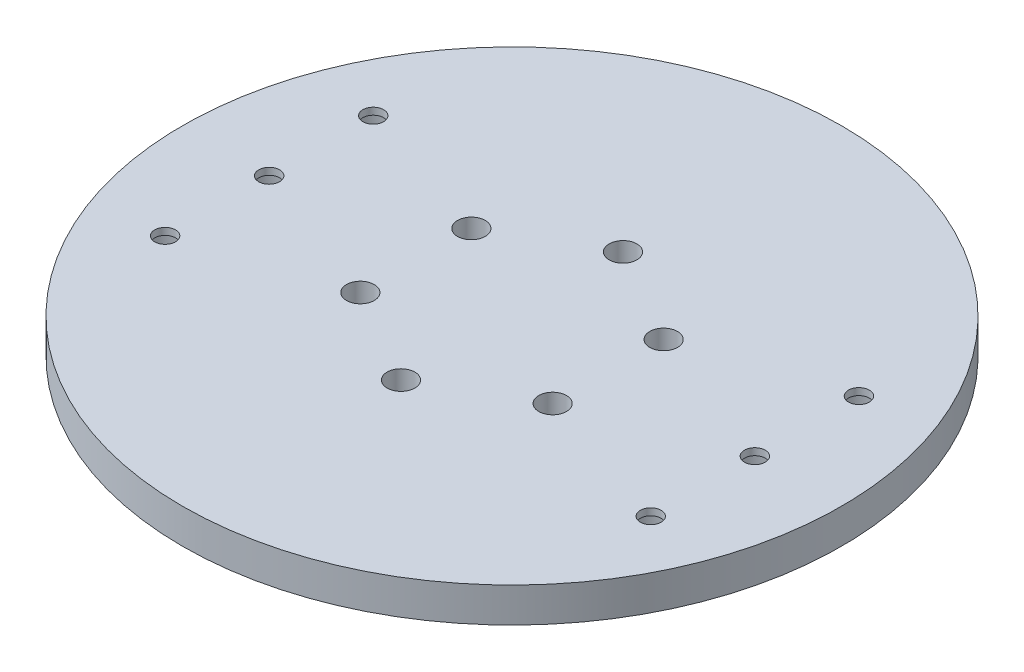
SolidWorks part; units mm, degrees
ref_plane "Alzado" through (0, 0, 0) normal (0, 0, 1) x (1, 0, 0)
ref_plane "Planta" through (0, 0, 0) normal (0, 1, 0) x (1, 0, 0)
ref_plane "Vista lateral" through (0, 0, 0) normal (1, 0, 0) x (0, 0, -1)
sketch "Croquis1" plane through (0, 0, 0) normal (0, 1, 0) x (1, 0, 0)
  circle A0 centre (0, 0) radius 24.5
  dimension "D1" = 49
extrude "Saliente-Extruir1" add sketch "Croquis1" along normal blind 3.7
sketch "Croquis2" plane through (0, 3.7, 0) normal (0, 1, 0) x (1, 0, 0)
  circle A0 centre (0, 0) radius 16 construction
  circle A1 centre (0, 16) radius 2
  dimension "D1" = 32
  dimension "D2" = 4
extrude "Cortar-Extruir1" cut sketch "Croquis2" against normal through all
pattern_circular "MatrizC1" count 6 over 360 about axis through (0, 0, 0) along (0, 1, 0) of "Cortar-Extruir1"
sketch "Croquis3" plane through (0, 3.7, 0) normal (0, 1, 0) x (1, 0, 0)
  circle A1 centre (0, 0) radius 47.5
  circle A2 centre (13.8564, 8) radius 2 construction
  circle A3 centre (13.8564, -8) radius 2 construction
  circle A4 centre (0, -16) radius 2 construction
  circle A5 centre (-13.8564, -8) radius 2 construction
  circle A6 centre (-13.8564, 8) radius 2 construction
  circle A7 centre (0, 16) radius 2 construction
  circle A8 centre (13.8564, 8) radius 2
  circle A9 centre (13.8564, -8) radius 2
  circle A10 centre (0, -16) radius 2
  circle A11 centre (-13.8564, -8) radius 2
  circle A12 centre (-13.8564, 8) radius 2
  circle A13 centre (0, 16) radius 2
  dimension "D1" = 95
extrude "Saliente-Extruir2" add sketch "Croquis3" along normal blind 5
sketch "Croquis4" plane through (0, 8.7, 0) normal (0, 1, 0) x (1, 0, 0)
  line L1 (-30, -20) -> (30, -20)
  line L2 (-30, -20) -> (-30, 20)
  line L3 (-30, 20) -> (30, 20)
  line L4 (30, -20) -> (30, 20)
  line L5 (-30, -20) -> (30, 20) construction
  line L6 (-30, 20) -> (30, -20) construction
  point P0 (0, 0)
  dimension "D1" = 40
  dimension "D2" = 60
sketch "Croquis6" plane through (0, 8.7, 0) normal (0, 1, 0) x (1, 0, 0)
  line L0 (-30, -20) -> (-35, -20) construction
  line L1 (-35, -20) -> (-35, 50) construction
  line L5 (-30, 20) -> (30, 20) construction
  circle A2 centre (-35, 15) radius 1.5
  circle A3 centre (-35, 0) radius 1.5
  circle A4 centre (-35, -15) radius 1.5
  dimension "D3" = 5
  dimension "D6" = 3
  dimension "D1" = 5
  dimension "D2" = 70
  dimension "D4" = 5
  dimension "D5" = 15
  dimension "D7" = 15
extrude "Cortar-Extruir2" cut sketch "Croquis6" against normal through all
mirror "Simetría1" about plane through (0, 0, 0) normal (1, 0, 0) of "Cortar-Extruir2"
sketch "Croquis7" plane through (0, 3.7, 0) normal (0, -1, 0) x (1, 0, 0)
  circle A0 centre (35, 15) radius 1.5 construction
  circle A1 centre (35, 0) radius 1.5 construction
  circle A2 centre (35, -15) radius 1.5 construction
  circle A5 centre (-35, -15) radius 1.5 construction
  circle A6 centre (-35, 0) radius 1.5 construction
  circle A7 centre (-35, 15) radius 1.5 construction
  circle A8 centre (35, 15) radius 1.5
  circle A9 centre (35, 0) radius 1.5
  circle A10 centre (35, -15) radius 1.5
  circle A13 centre (-35, -15) radius 1.5
  circle A14 centre (-35, 0) radius 1.5
  circle A15 centre (-35, 15) radius 1.5
  circle A16 centre (35, 15) radius 3.5
  circle A17 centre (35, 0) radius 3.5
  circle A18 centre (35, -15) radius 3.5
  circle A20 centre (-35, 15) radius 3.5
  circle A21 centre (-35, 0) radius 3.5
  circle A22 centre (-35, -15) radius 3.5
  dimension "D1" = 2
extrude "Cortar-Extruir3" cut sketch "Croquis7" against normal blind 4
